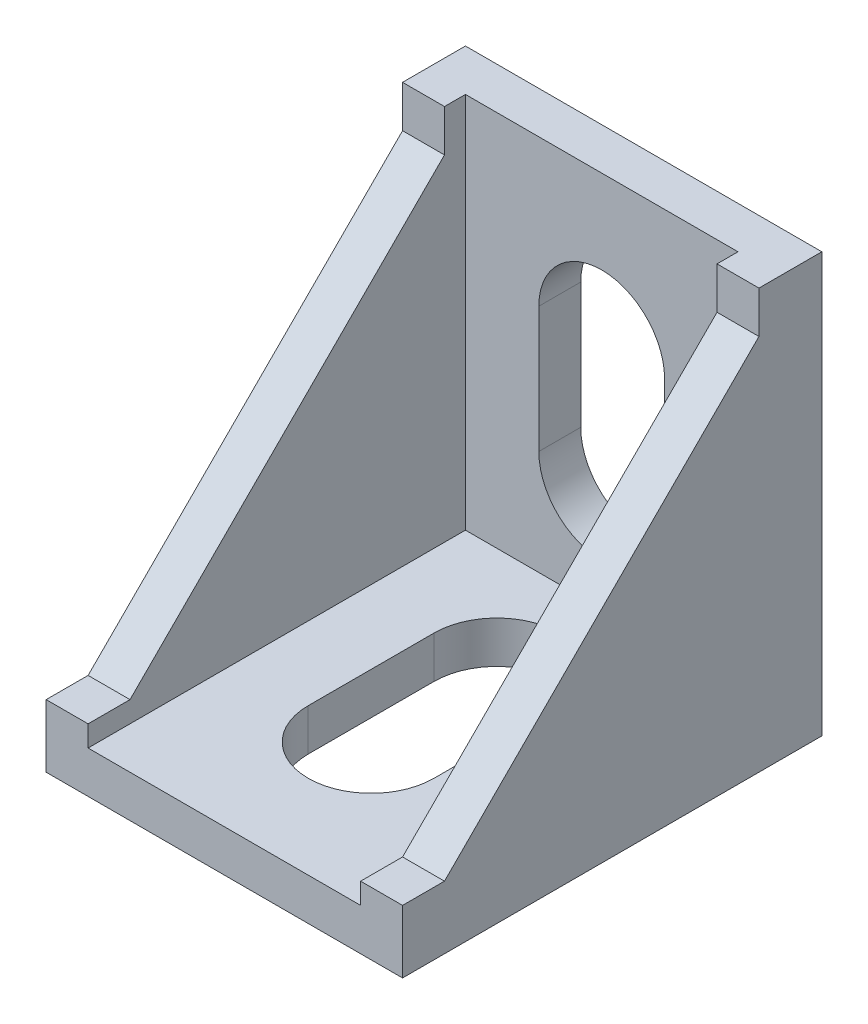
SolidWorks part; units mm, degrees
material "1060 Alloy"
ref_plane "Front Plane" through (0, 0, 0) normal (0, 0, 1) x (1, 0, 0)
ref_plane "Top Plane" through (0, 0, 0) normal (0, 1, 0) x (1, 0, 0)
ref_plane "Right Plane" through (0, 0, 0) normal (1, 0, 0) x (0, 0, -1)
ref_plane "BaseLevelPlane" through (0, 2, 0) normal (0, 1, 0) x (1, 0, 0)
ref_plane "TopLevelPlane" through (0, 20, 0) normal (0, 1, 0) x (1, 0, 0)
ref_plane "Left Side Plane" through (17, 0, 0) normal (1, 0, 0) x (0, 0, -1)
ref_plane "Rear Plane" through (0, 0, -20) normal (0, 0, 1) x (1, 0, 0)
sketch "Master Sketch" plane through (0, 0, 0) normal (0, 1, 0) x (1, 0, 0)
  line L0 (2, 0) -> (2, 18)
  line L1 (0, 0) -> (2, 0)
  line L2 (0, 0) -> (0, 20)
  line L3 (0, 20) -> (17, 20)
  line L4 (17, 0) -> (17, 20)
  line L5 (2, 18) -> (15, 18)
  line L6 (15, 18) -> (15, 0)
  line L7 (15, 0) -> (17, 0)
  line L8 (2, 0) -> (15, 0)
  line L9 (2, 18) -> (2, 20) construction
  line L10 (0, 10) -> (17, 10) construction
  line L11 (7, 19) -> (10, 19)
  line L13 (7, 17) -> (10, 17)
  line L15 (7, 19) -> (10, 17) construction
  line L16 (7, 17) -> (10, 19) construction
  line L17 (7, 1) -> (10, 1)
  line L18 (7, 3) -> (10, 3)
  arc A0 (7, 19) -> (7, 17) centre (7, 18) ccw
  arc A1 (10, 17) -> (10, 19) centre (10, 18) ccw
  arc A2 (7, 1) -> (7, 3) centre (7, 2) cw
  arc A3 (10, 3) -> (10, 1) centre (10, 2) cw
  point P10 (8.5, 18)
  dimension "D4" = 3
  dimension "D5" = 1
  dimension "D1" = 20
  dimension "D2" = 17
  dimension "D3" = 2
  dimension "D6" = 8.5
  dimension "D7" = 18
sketch "Base Sketch" plane through (0, 0, 0) normal (0, 1, 0) x (1, 0, 0)
  line L0 (0, 0) -> (2, 0) construction
  line L1 (2, 0) -> (15, 0) construction
  line L2 (15, 0) -> (17, 0) construction
  line L3 (17, 0) -> (17, 20) construction
  line L4 (0, 20) -> (17, 20) construction
  line L5 (0, 0) -> (0, 20) construction
  line L6 (0, 0) -> (2, 0)
  line L7 (2, 0) -> (15, 0)
  line L8 (15, 0) -> (17, 0)
  line L9 (17, 0) -> (17, 20)
  line L10 (0, 20) -> (17, 20)
  line L11 (0, 0) -> (0, 20)
  line L14 (5.5, 13) -> (5.5, 7)
  line L16 (11.5, 13) -> (11.5, 7)
  line L17 (5.5, 13) -> (11.5, 7) construction
  line L18 (5.5, 7) -> (11.5, 13) construction
  arc A0 (5.5, 13) -> (11.5, 13) centre (8.5, 13) cw
  arc A1 (5.5, 7) -> (11.5, 7) centre (8.5, 7) ccw
  point P2 (8.5, 10)
  dimension "D1" = 6
  dimension "D2" = 6
  dimension "D3" = 8.5
  dimension "D4" = 10
extrude "Base" add sketch "Base Sketch" along normal up to surface (2 mm away) up to plane "BaseLevelPlane"
sketch "MainUprightSketch" plane through (0, 2, 0) normal (0, 1, 0) x (1, 0, 0)
  line L0 (17, 0) -> (17, 20) construction
  line L1 (15, 0) -> (17, 0) construction
  line L2 (15, 18) -> (15, 0) construction
  line L3 (2, 18) -> (15, 18) construction
  line L4 (0, 20) -> (17, 20) construction
  line L5 (0, 0) -> (2, 0) construction
  line L6 (2, 0) -> (2, 18) construction
  line L7 (0, 0) -> (0, 20) construction
  line L8 (17, 0) -> (17, 20)
  line L9 (15, 0) -> (17, 0)
  line L10 (15, 18) -> (15, 0)
  line L11 (2, 18) -> (15, 18)
  line L12 (0, 20) -> (17, 20)
  line L13 (0, 0) -> (2, 0)
  line L14 (2, 0) -> (2, 18)
  line L15 (0, 0) -> (0, 20)
extrude "Sides" add sketch "MainUprightSketch" along normal up to surface (18 mm away) up to plane "TopLevelPlane"
sketch "NubsSketch" plane through (0, 0, 0) normal (0, 1, 0) x (1, 0, 0)
  line L0 (7, 19) -> (10, 19) construction
  line L1 (7, 17) -> (10, 17) construction
  line L2 (7, 1) -> (10, 1) construction
  line L3 (7, 3) -> (10, 3) construction
  line L4 (7, 19) -> (10, 19)
  line L5 (7, 17) -> (10, 17)
  line L6 (7, 1) -> (10, 1)
  line L7 (7, 3) -> (10, 3)
  arc A0 (7, 19) -> (7, 17) centre (7, 18) ccw construction
  arc A1 (10, 17) -> (10, 19) centre (10, 18) ccw construction
  arc A2 (10, 1) -> (10, 3) centre (10, 2) ccw construction
  arc A3 (7, 3) -> (7, 1) centre (7, 2) ccw construction
  arc A4 (7, 19) -> (7, 17) centre (7, 18) ccw
  arc A5 (10, 17) -> (10, 19) centre (10, 18) ccw
  arc A6 (10, 1) -> (10, 3) centre (10, 2) ccw
  arc A7 (7, 3) -> (7, 1) centre (7, 2) ccw
extrude "Nubs-Bottom" add sketch "NubsSketch" against normal blind 1
sketch "RearNubsSketch" plane through (0, 0, -20) normal (0, 0, 1) x (1, 0, 0)
  line L0 (7, 0) -> (10, 0) construction
  line L1 (7, 0) -> (10, 0) construction
  line L3 (10, 3) -> (7, 3)
  line L5 (10, 1) -> (7, 1)
  line L7 (10, 3) -> (7, 1) construction
  line L8 (10, 1) -> (7, 3) construction
  line L9 (17, 10) -> (0, 10) construction
  line L10 (10, 19) -> (7, 19)
  line L11 (10, 17) -> (7, 17)
  arc A0 (10, 3) -> (10, 1) centre (10, 2) cw
  arc A1 (7, 1) -> (7, 3) centre (7, 2) cw
  arc A2 (10, 17) -> (10, 19) centre (10, 18) ccw
  arc A3 (7, 19) -> (7, 17) centre (7, 18) ccw
  point P2 (8.5, 2)
  dimension "D1" = 1
  dimension "D2" = 10
  dimension "D3" = 2
extrude "Nubs-Rear" add sketch "RearNubsSketch" against normal blind 1
sketch "Cutaway Sketch" plane through (0, 0, 0) normal (1, 0, 0) x (0, 0, -1)
  line L1 (0, 3) -> (2, 3)
  line L2 (2, 3) -> (17, 18)
  line L3 (17, 18) -> (17, 20)
  line L6 (17, 20) -> (0, 20)
  line L7 (0, 20) -> (0, 3)
  dimension "D1" = 3
  dimension "D2" = 20
  dimension "D3" = 2
  dimension "D4" = 45
extrude "Side Cut" cut sketch "Cutaway Sketch" along normal up to surface (17 mm away) up to plane "Left Side Plane"
sketch "RearSlotSketch" plane through (0, 0, -20) normal (0, 0, 1) x (1, 0, 0)
  line L2 (5.5, 13) -> (5.5, 7)
  line L4 (11.5, 13) -> (11.5, 7)
  line L5 (5.5, 13) -> (11.5, 7) construction
  line L6 (5.5, 7) -> (11.5, 13) construction
  arc A0 (5.5, 13) -> (11.5, 13) centre (8.5, 13) cw
  arc A1 (5.5, 7) -> (11.5, 7) centre (8.5, 7) ccw
  point P0 (8.5, 10)
  dimension "D1" = 3
  dimension "D2" = 6
  dimension "D3" = 10
  dimension "D4" = 8.5
extrude "Rear Slot" cut sketch "RearSlotSketch" along normal through all
